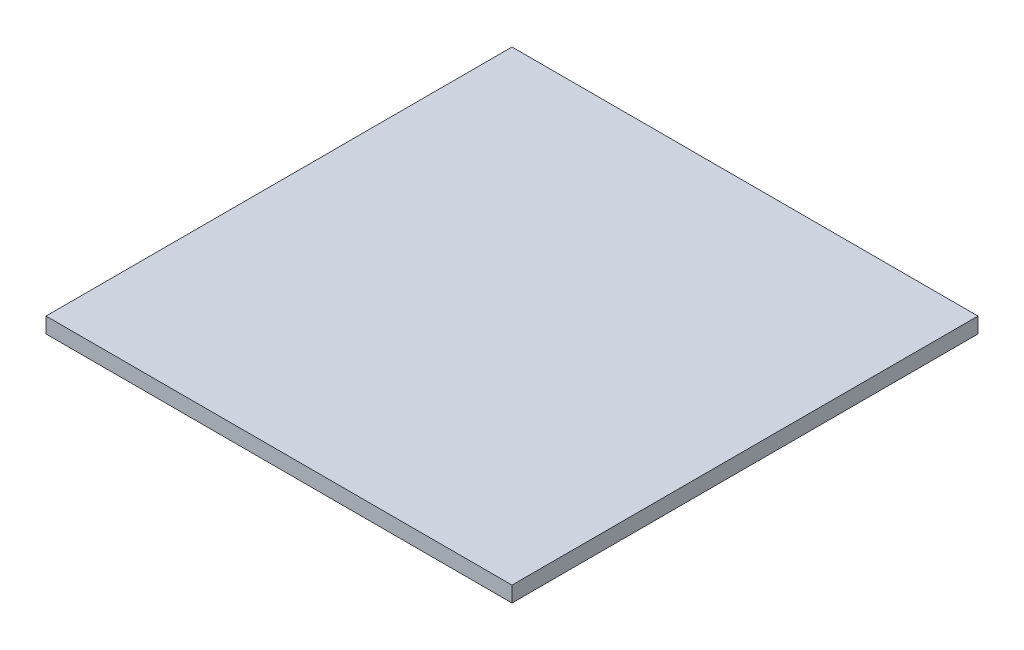
SolidWorks part; units mm, degrees
material "Beton"
ref_plane "Ebene vorne" through (0, 0, 0) normal (0, 0, 1) x (1, 0, 0)
ref_plane "Ebene oben" through (0, 0, 0) normal (0, 1, 0) x (1, 0, 0)
ref_plane "Ebene rechts" through (0, 0, 0) normal (1, 0, 0) x (0, 0, -1)
sketch "Skizze1" plane through (0, 0, 0) normal (0, 1, 0) x (1, 0, 0)
  line L1 (-28276.4415, 1169.1176) -> (1723.5585, 1169.1176)
  line L2 (-28276.4415, 1169.1176) -> (-28276.4415, -28830.8824)
  line L3 (-28276.4415, -28830.8824) -> (1723.5585, -28830.8824)
  line L4 (1723.5585, 1169.1176) -> (1723.5585, -28830.8824)
  dimension "D1" = 30000
  dimension "D2" = 30000
extrude "Aufsatz-Linear austragen1" add sketch "Skizze1" along normal blind 1000
